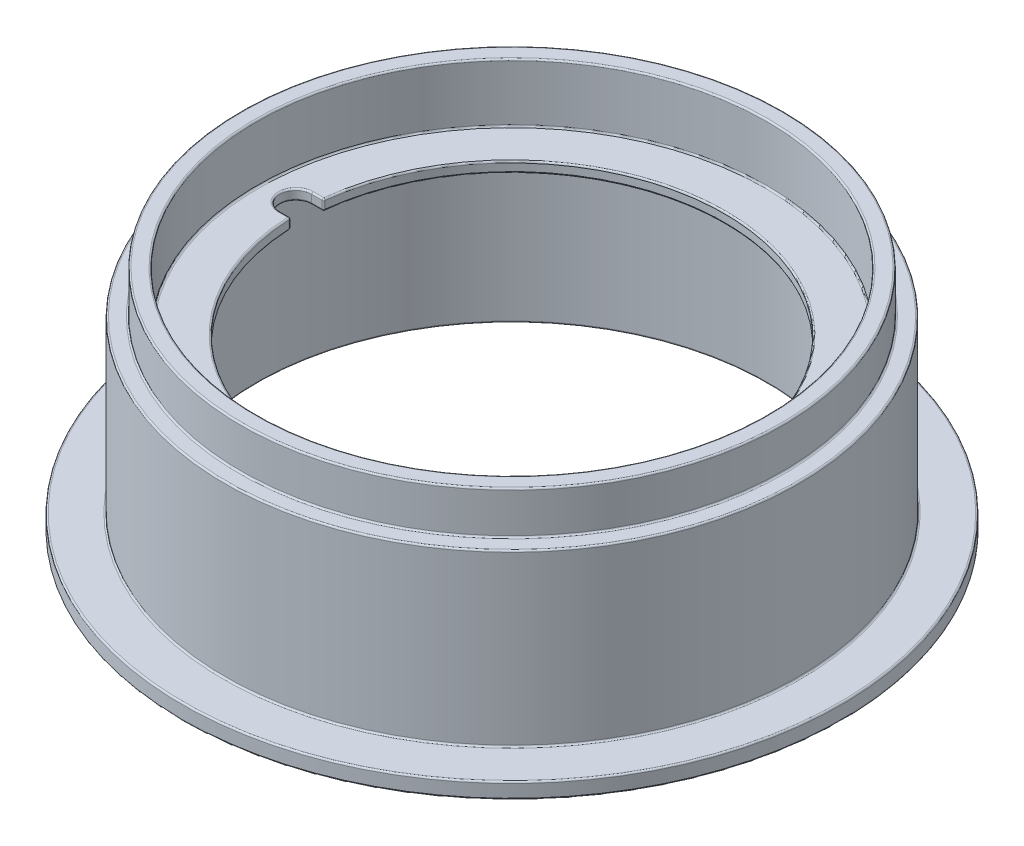
SolidWorks part; units mm, degrees
ref_plane "Front Plane" through (0, 0, 0) normal (0, 0, 1) x (1, 0, 0)
ref_plane "Top Plane" through (0, 0, 0) normal (0, 1, 0) x (1, 0, 0)
ref_plane "Right Plane" through (0, 0, 0) normal (1, 0, 0) x (0, 0, -1)
sketch "Sketch1" plane through (0, 0, 0) normal (0, 0, 1) x (1, 0, 0)
  line L0 (0, 0) -> (0, 9.2137) construction
  line L1 (-12, 0) -> (-15.5, 0)
  line L2 (-15.5, 0) -> (-15.5, 0.75)
  line L3 (-15.5, 0.75) -> (-13.5, 0.75)
  line L4 (-13.5, 0.75) -> (-13.5, 8.75)
  line L5 (-13.5, 8.75) -> (-12.75, 8.75)
  line L6 (-12.75, 8.75) -> (-12.75, 10.75)
  line L7 (-12.75, 10.75) -> (-12, 10.75)
  line L8 (-12, 10.75) -> (-12, 8)
  line L9 (-12, 8) -> (-10, 8)
  line L10 (-10, 8) -> (-10, 7.5)
  line L11 (-10, 7.5) -> (-12, 7.5)
  line L12 (-12, 7.5) -> (-12, 0)
  dimension "D1" = 13.5
  dimension "D2" = 8
  dimension "D3" = 0.75
  dimension "D4" = 2
  dimension "D5" = 2
  dimension "D6" = 0.75
  dimension "D7" = 0.75
  dimension "D8" = 0.5
  dimension "D9" = 7.5
  dimension "D10" = 2
revolve "Revolve1" add sketch "Sketch1" angle 360 about L0
sketch "Sketch2" plane through (0, 0, 0) normal (0, 1, 0) x (1, 0, 0)
  line L0 (0, 0) -> (0, 4.0608) construction
  line L1 (-8.5, -0.4183) -> (-8.5, 1.0817)
  line L2 (-8.5, 1.0817) -> (-10.5, 1.0817)
  line L4 (-10.5, -0.4183) -> (-8.5, -0.4183)
  line L5 (10.5, -0.4183) -> (8.5, -0.4183)
  line L6 (8.5, -0.4183) -> (8.5, 1.0817)
  line L7 (8.5, 1.0817) -> (10.5, 1.0817)
  arc A1 (-10.5, -0.4183) -> (-10.5, 1.0817) centre (-10.5, 0.3317) cw
  arc A2 (10.5, -0.4183) -> (10.5, 1.0817) centre (10.5, 0.3317) ccw
  dimension "D1" = 8.5
  dimension "D2" = 1.5
  dimension "D3" = 2
extrude "Cut-Extrude1" cut sketch "Sketch2" along normal up to surface (8 mm away) up to face at (0, 8, -12)
fillet "Fillet1" radius 0.075 30 edges at (10.2456, 8, 0.4183) (10.2207, 8, -1.0817) (11.25, 8, -0.3317) (-11.25, 8, -0.3317) (-10.2207, 8, -1.0817) (-10.2456, 8, 0.4183) (9.9413, 7.75, -1.0817) (9.9912, 7.75, 0.4183) (-9.9912, 7.75, 0.4183) (-9.9413, 7.75, -1.0817) (0, 7.5, -12) (0, 7.5, -10) (0, 7.5, 10) (0, 8, -10) (0, 8, 10) (0, 8, -12) (0, 10.75, -12) (0, 10.75, -12.75) (0, 8.75, -12.75) (0, 0.75, -13.5) (0, 0.75, -15.5) (0, 0, -15.5) (0, 0, -12) (11.25, 7.5, -0.3317) (10.2207, 7.5, -1.0817) (10.2456, 7.5, 0.4183) (-10.2456, 7.5, 0.4183) (-11.25, 7.5, -0.3317) (-10.2207, 7.5, -1.0817) (0, 8.75, -13.5)
